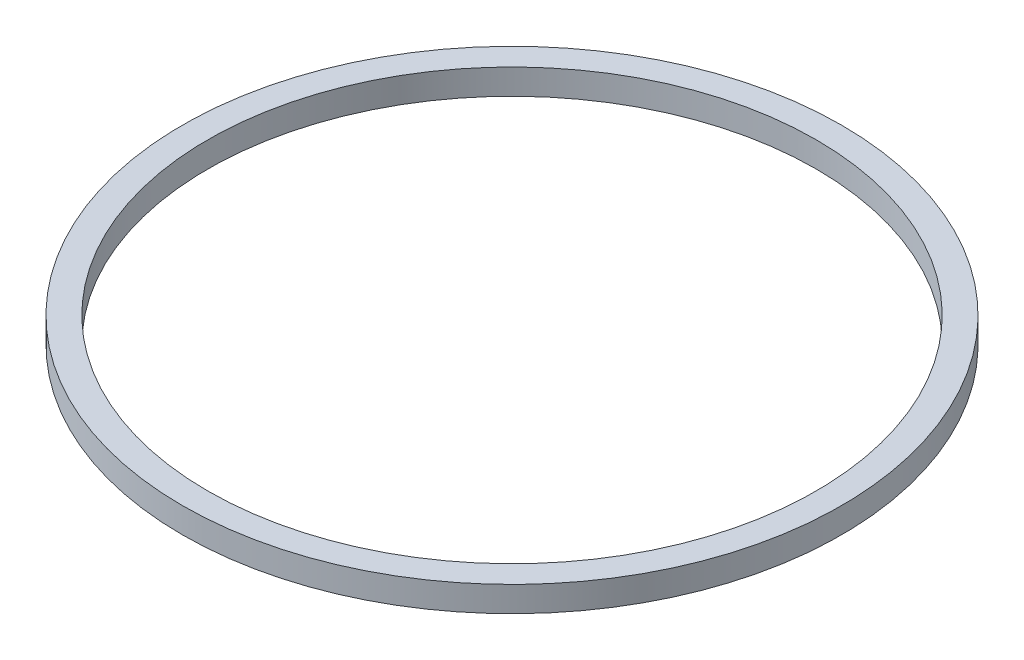
SolidWorks part; units mm, degrees
material "PLA"
ref_plane "Front Plane" through (0, 0, 0) normal (0, 0, 1) x (1, 0, 0)
ref_plane "Top Plane" through (0, 0, 0) normal (0, 1, 0) x (1, 0, 0)
ref_plane "Right Plane" through (0, 0, 0) normal (1, 0, 0) x (0, 0, -1)
sketch "Sketch1" plane through (0, 0, 0) normal (0, 1, 0) x (1, 0, 0)
  circle A0 centre (0, 0) radius 75
  circle A1 centre (0, 0) radius 62.3
  dimension "D1" = 150
  dimension "D2" = 124.6
extrude "Boss-Extrude1" add sketch "Sketch1" along normal blind 53
sketch "Sketch2" plane through (0, 0, 0) normal (0, -1, 0) x (1, 0, 0)
  circle A0 centre (0, 0) radius 75
  circle A1 centre (0, 0) radius 48
  dimension "D1" = 96
ref_plane "Plane1" through (0, 20, 0) normal (0, -1, 0) x (-1, 0, 0)
sketch "Sketch3" plane through (0, 20, 0) normal (0, -1, 0) x (-1, 0, 0)
  circle A0 centre (0, 0) radius 75
  circle A1 centre (0, 0) radius 47
  dimension "96" = 94
extrude "Boss-Extrude3" add sketch "Sketch3" along normal blind 3
sketch "Sketch4" plane through (0, 17, 0) normal (0, -1, 0) x (1, 0, 0)
  circle A0 centre (0, 0) radius 50.1
  circle A1 centre (0, 0) radius 47
  dimension "D1" = 100.2
extrude "Boss-Extrude4" add sketch "Sketch4" along normal blind 14
sketch "Sketch5" plane through (0, 17, 0) normal (0, -1, 0) x (1, 0, 0)
  circle A0 centre (0, 0) radius 62.3
  circle A1 centre (0, 0) radius 50.1
extrude "Boss-Extrude5" add sketch "Sketch5" along normal blind 1
sketch "Sketch6" plane through (0, 53, 0) normal (0, 1, 0) x (1, 0, 0)
  circle A2 centre (0, 0) radius 67.5
  circle A3 centre (0, 0) radius 75
  dimension "D1" = 135
extrude "Cut-Extrude2" cut sketch "Sketch6" against normal blind 64
sketch "Sketch7" plane through (0, 53, 0) normal (0, 1, 0) x (1, 0, 0)
  circle A0 centre (0, 0) radius 60
  circle A1 centre (0, 0) radius 62.3
  dimension "D1" = 120
extrude "Boss-Extrude6" add sketch "Sketch7" against normal up to surface (53 mm away) up to face at (0, 0, 62.3)
sketch "Sketch9" plane through (0, 3, 0) normal (0, -1, 0) x (1, 0, 0)
  circle A0 centre (0, 0) radius 50.1
  circle A1 centre (0, 0) radius 47
extrude "Cut-Extrude3" cut sketch "Sketch9" against normal up to surface (17 mm away) up to face at (0, 20, -47)
sketch "Sketch10" plane through (0, 20, 0) normal (0, 1, 0) x (1, 0, 0)
  circle A0 centre (0, 0) radius 50.1
  circle A1 centre (0, 0) radius 48.5
  dimension "D1" = 97
extrude "Boss-Extrude7" add sketch "Sketch10" against normal up to surface (4 mm away) up to face at (0, 16, -50.1)
sketch "Sketch11" plane through (0, 16, 0) normal (0, -1, 0) x (1, 0, 0)
  circle A0 centre (0, 0) radius 47.6
  circle A1 centre (0, 0) radius 45.1
  dimension "D1" = 95.2
  dimension "D2" = 90.2
sketch "Sketch12" plane through (0, 16, 0) normal (0, -1, 0) x (1, 0, 0)
  circle A0 centre (0, 0) radius 47.6
  circle A1 centre (0, 0) radius 48.5
extrude "Boss-Extrude8" add sketch "Sketch12" against normal up to surface (4 mm away) up to face at (0, 20, -60)
sketch "Sketch13" plane through (0, 20, 0) normal (0, 1, 0) x (1, 0, 0)
  circle A0 centre (0, 0) radius 45.1
  circle A1 centre (0, 0) radius 47.6
extrude "Boss-Extrude9" add sketch "Sketch13" against normal blind 17
sketch "Sketch14" plane through (0, 0, 0) normal (0, -1, 0) x (1, 0, 0)
  circle A0 centre (0, 0) radius 75.9975
extrude "Cut-Extrude4" cut sketch "Sketch14" against normal blind 48
sketch "Sketch15" plane through (0, 53, 0) normal (0, 1, 0) x (1, 0, 0)
  circle A0 centre (0, 0) radius 65
  circle A1 centre (0, 0) radius 79.6374
  dimension "D1" = 130
extrude "Cut-Extrude5" cut sketch "Sketch15" against normal blind 50
